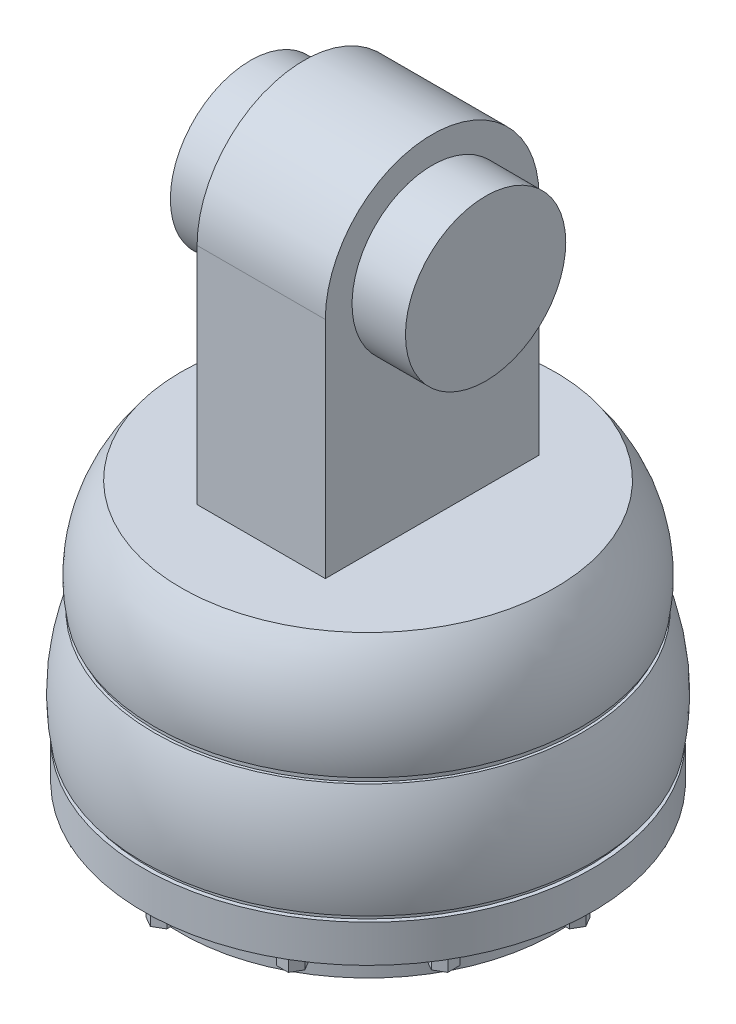
SolidWorks part; units mm, degrees
ref_plane "Front Plane" through (0, 0, 0) normal (0, 0, 1) x (1, 0, 0)
ref_plane "Top Plane" through (0, 0, 0) normal (0, 1, 0) x (1, 0, 0)
ref_plane "Right Plane" through (0, 0, 0) normal (1, 0, 0) x (0, 0, -1)
sketch "Sketch1" plane through (0, 0, 0) normal (0, 0, 1) x (1, 0, 0)
  line L0 (-35, 0) -> (0, 0)
  line L1 (0, 0) -> (0, -20)
  line L2 (0, -20) -> (-40, -20)
  arc A0 (-35, 0) -> (-40, -20) centre (-15.404, -15.524) ccw
  dimension "D4" = 25
  dimension "D1" = 35
  dimension "D2" = 20
  dimension "D3" = 40
revolve "Revolve1" add sketch "Sketch1" angle 360 about L1
sketch "Sketch2" plane through (0, -20, 0) normal (0, -1, 0) x (1, 0, 0)
  circle A0 centre (0, 0) radius 39.5
  dimension "D1" = 79
extrude "Boss-Extrude1" add sketch "Sketch2" along normal blind 1
sketch "Sketch3" plane through (0, 0, 0) normal (1, 0, 0) x (0, 0, -1)
  line L0 (0, -21) -> (-40, -21)
  line L1 (-39.5, -21) -> (39.5, -21) construction
  line L2 (0, -21) -> (0, -41)
  line L3 (0, -41) -> (-42, -41)
  arc A0 (-40, -21) -> (-42, -41) centre (-5.5677, -34.5432) ccw
  dimension "D4" = 37
  dimension "D1" = 40
  dimension "D2" = 20
  dimension "D3" = 42
revolve "Revolve2" add sketch "Sketch3" angle 360 about L2
sketch "Sketch4" plane through (0, -41, 0) normal (0, -1, 0) x (1, 0, 0)
  circle A0 centre (0, 0) radius 41.25
  dimension "D1" = 82.5
extrude "Boss-Extrude2" add sketch "Sketch4" along normal blind 1
sketch "Sketch5" plane through (0, -42, 0) normal (0, -1, 0) x (1, 0, 0)
  circle A0 centre (0, 0) radius 42
  dimension "D1" = 84
extrude "Boss-Extrude3" add sketch "Sketch5" along normal blind 7
sketch "Sketch6" plane through (0, -49, 0) normal (0, -1, 0) x (1, 0, 0)
  circle A0 centre (0, 0) radius 35
  dimension "D1" = 70
extrude "Boss-Extrude4" add sketch "Sketch6" along normal blind 7
sketch "Sketch7" plane through (0, -49, 0) normal (0, -1, 0) x (1, 0, 0)
  line L0 (35, 0) -> (42, 0) construction
  line L1 (39.0476, 0.9486) -> (37.9524, 0.9486)
  line L2 (36.25, 0) -> (37.375, -1.9486)
  line L3 (37.375, -1.9486) -> (39.625, -1.9486)
  line L4 (39.625, -1.9486) -> (40.75, 0)
  line L5 (40.75, 0) -> (39.625, 1.9486)
  line L6 (39.625, 1.9486) -> (37.375, 1.9486)
  line L7 (37.375, 1.9486) -> (36.25, 0)
  line L8 (37.9524, 0.9486) -> (37.4047, 0)
  line L9 (37.4047, 0) -> (37.9524, -0.9486)
  line L10 (37.9524, -0.9486) -> (39.0476, -0.9486)
  line L11 (39.0476, -0.9486) -> (39.5953, 0)
  line L12 (39.5953, 0) -> (39.0476, 0.9486)
  circle A0 centre (0, 0) radius 35 construction
  circle A1 centre (0, 0) radius 35 construction
  circle A2 centre (0, 0) radius 42 construction
  circle A3 centre (38.5, 0) radius 1.9486 construction
  dimension "D1" = 4.5
  dimension "D2" = 1
extrude "Boss-Extrude5" add sketch "Sketch7" along normal blind 3
pattern_circular "CirPattern1" count 12 over 360 about axis through (0, 0, 0) along (0, 1, 0) of "Boss-Extrude5"
sketch "Sketch8" plane through (0, -56, 0) normal (0, -1, 0) x (1, 0, 0)
  circle A0 centre (0, 0) radius 15
  dimension "D1" = 30
extrude "Boss-Extrude6" add sketch "Sketch8" along normal blind 10
sketch "Sketch9" plane through (0, 0, 0) normal (0, 1, 0) x (1, 0, 0)
  line L1 (-12, -20) -> (12, -20)
  line L2 (-12, -20) -> (-12, 20)
  line L3 (-12, 20) -> (12, 20)
  line L4 (12, -20) -> (12, 20)
  line L5 (-12, -20) -> (12, 20) construction
  line L6 (-12, 20) -> (12, -20) construction
  point P0 (0, 0)
  dimension "D1" = 24
  dimension "D2" = 40
extrude "Boss-Extrude7" add sketch "Sketch9" along normal blind 42
sketch "Sketch10" plane through (12, 0, 0) normal (1, 0, 0) x (0, 0, -1)
  line L0 (-20, 42) -> (20, 42) construction
  line L1 (-20, 42) -> (20, 42)
  arc A0 (20, 42) -> (-20, 42) centre (0, 42) ccw
  dimension "D1" = 40
extrude "Boss-Extrude8" add sketch "Sketch10" against normal up to vertex
sketch "Sketch11" plane through (-12, 0, 0) normal (-1, 0, 0) x (0, 0, 1)
  circle A0 centre (0, 42) radius 15
  dimension "D1" = 30
extrude "Boss-Extrude9" add sketch "Sketch11" along normal blind 10
sketch "Sketch12" plane through (12, 0, 0) normal (1, 0, 0) x (0, 0, -1)
  circle A0 centre (0, 42) radius 15
  dimension "D1" = 30
extrude "Boss-Extrude10" add sketch "Sketch12" along normal blind 10
